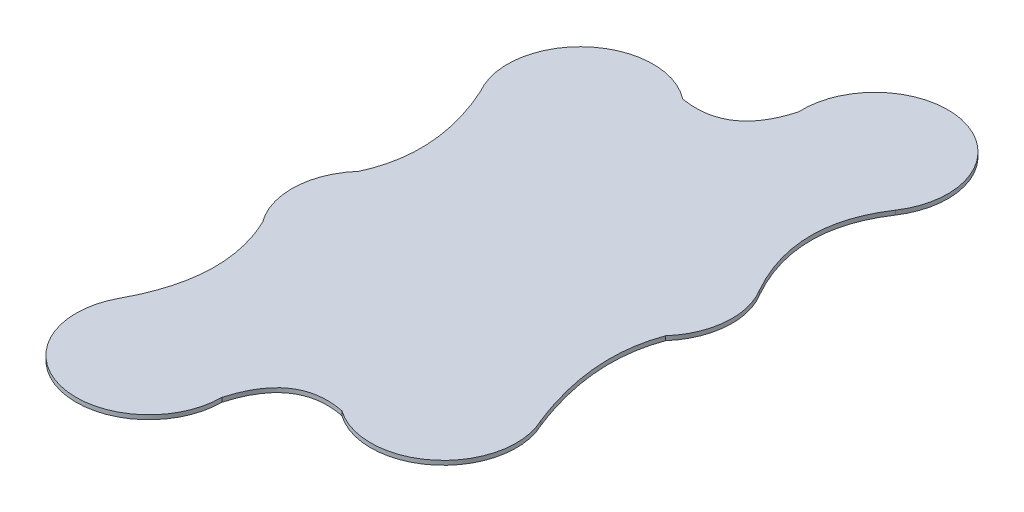
SolidWorks part; units mm, degrees
ref_plane "Front Plane" through (0, 0, 0) normal (0, 0, 1) x (1, 0, 0)
ref_plane "Top Plane" through (0, 0, 0) normal (0, 1, 0) x (1, 0, 0)
ref_plane "Right Plane" through (0, 0, 0) normal (1, 0, 0) x (0, 0, -1)
sketch "Sketch3" plane through (0, 0, 0) normal (0, 1, 0) x (1, 0, 0)
  line L0 (-48.7944, -96.3842) -> (-44.3788, -88.2223) construction
  line L1 (-44.3788, -88.2223) -> (-48.1377, -80.3528) construction
  line L2 (-47.6613, -69.6204) -> (-44.6779, -63.1595) construction
  line L3 (-44.6779, -63.1595) -> (-48.6384, -54.4492) construction
  line L4 (-36.0838, -43.4317) -> (-29.8317, -44.5112) construction
  line L5 (-29.8317, -44.5112) -> (-28.0269, -37.9832) construction
  line L6 (-12.4542, -42.252) -> (-17.2525, -49.4864) construction
  line L7 (-17.2525, -49.4864) -> (-12.3178, -58.2179) construction
  line L8 (-13.1644, -68.3279) -> (-15.5868, -74.861) construction
  line L9 (-15.5868, -74.861) -> (-11.8656, -84.1948) construction
  line L10 (-32.8183, -100.4288) -> (-30.8469, -93.4706) construction
  line L11 (-30.8469, -93.4706) -> (-24.4458, -94.7936) construction
  arc A6 (-36.0838, -43.4317) -> (-48.6384, -54.4492) centre (-41.3183, -50.1288) ccw
  arc A7 (-47.6613, -69.6204) -> (-48.1377, -80.3528) centre (-41.3183, -75.2788) ccw
  arc A8 (-48.7944, -96.3842) -> (-32.8183, -100.4288) centre (-41.3183, -100.4288) ccw
  arc A9 (-24.4458, -94.7936) -> (-11.8656, -84.1948) centre (-19.5378, -87.8538) ccw
  arc A10 (-13.1644, -68.3279) -> (-12.3178, -58.2179) centre (-19.5378, -62.7038) ccw
  arc A11 (-12.4542, -42.252) -> (-28.0269, -37.9832) centre (-19.5378, -37.5538) ccw
  spline S0 degree 2 poles (-48.7944, -96.3842) (-44.3788, -88.2223) (-48.1377, -80.3528) knots 0 0 0 1 1 1
  spline S1 degree 2 poles (-47.6613, -69.6204) (-44.6779, -63.1595) (-48.6384, -54.4492) knots 0 0 0 1 1 1
  spline S2 degree 2 poles (-36.0838, -43.4317) (-29.8317, -44.5112) (-28.0269, -37.9832) knots 0 0 0 1 1 1
  spline S3 degree 2 poles (-12.4542, -42.252) (-17.2525, -49.4864) (-12.3178, -58.2179) knots 0 0 0 1 1 1
  spline S4 degree 2 poles (-13.1644, -68.3279) (-15.5868, -74.861) (-11.8656, -84.1948) knots 0 0 0 1 1 1
  spline S5 degree 2 poles (-32.8183, -100.4288) (-30.8469, -93.4706) (-24.4458, -94.7936) knots 0 0 0 1 1 1
  dimension "D13" = 17
  dimension "D14" = 17
  dimension "D15" = 17
  dimension "D16" = 17
  dimension "D17" = 17
  dimension "D18" = 17
  dimension "D7" = 25.15
  dimension "D8" = 25.15
extrude "Boss-Extrude2" add sketch "Sketch3" along normal blind 0.5 contours A6 S1 A7 S0 A8 S5 A9 S4 A10 S3 A11 S2
sketch "Sketch4" plane through (0, 0.5, 0) normal (0, 1, 0) x (1, 0, 0)
  line L0 (-46.4079, -64.595) -> (-13.8326, -70.7451) construction
  parabola Q0 (-47.6613, -69.6204) -> (-48.6384, -54.4492) focus (-53.5695, -65.9825) apex (-47.0623, -68.0904) construction
  parabola Q1 (-13.1644, -68.3279) -> (-11.8656, -84.1948) focus (-6.2588, -70.3316) apex (-12.767, -67.3647) construction
